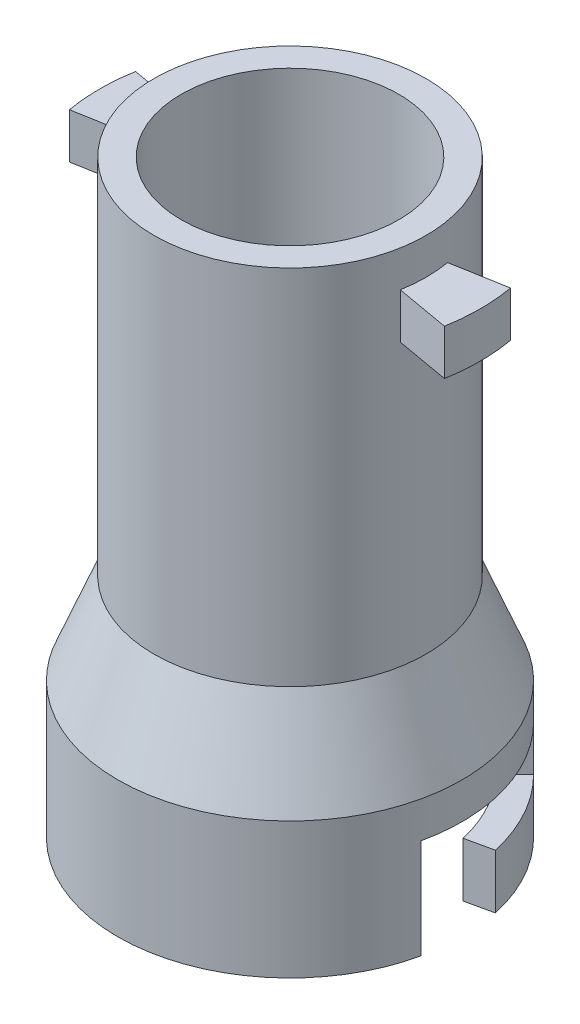
SolidWorks part; units mm, degrees
ref_plane "Front Plane" through (0, 0, 0) normal (0, 0, 1) x (1, 0, 0)
ref_plane "Top Plane" through (0, 0, 0) normal (0, 1, 0) x (1, 0, 0)
ref_plane "Right Plane" through (0, 0, 0) normal (1, 0, 0) x (0, 0, -1)
sketch "Sketch1" plane through (0, 0, 0) normal (0, 0, 1) x (1, 0, 0)
  line L0 (0, 40.4677) -> (0, -47.133) construction
  line L1 (12, 32) -> (12, -18)
  line L2 (16, -33) -> (19, -33)
  line L3 (19, -33) -> (19, -18)
  line L4 (19, -18) -> (15, -8)
  line L5 (15, -8) -> (15, 32)
  line L6 (15, 32) -> (12, 32)
  line L7 (12, -18) -> (16, -18)
  line L8 (16, -18) -> (16, -33)
  line L9 (-38.6492, 0) -> (68.272, 0) construction
  dimension "D1" = 3
  dimension "D2" = 16
  dimension "D3" = 15
  dimension "D4" = 3
  dimension "D5" = 15
  dimension "D6" = 10
  dimension "D7" = 50
  dimension "D8" = 32
revolve "Revolve1" add sketch "Sketch1" angle 360 about L0
ref_axis "Axis1" through (0, -42.0041, 0) along (0, 1, 0)
sketch "Sketch2" plane through (0, 0, 0) normal (0, 0, 1) x (1, 0, 0)
  line L0 (15, 28) -> (21, 28)
  line L1 (15, -8) -> (15, 32) construction
  line L2 (21, 28) -> (21, 23)
  line L3 (21, 23) -> (15, 23)
  line L4 (15, 23) -> (15, 28)
  line L5 (-15, 28) -> (-15, 23)
  line L6 (-15, 32) -> (-15, -8) construction
  line L7 (-15, 23) -> (-21, 23)
  line L8 (-21, 23) -> (-21, 28)
  line L9 (-21, 28) -> (-15, 28)
  line L10 (0, 45.3067) -> (0, -45.5409) construction
  line L11 (15, 32) -> (-15, 32) construction
  dimension "D1" = 6
  dimension "D2" = 6
  dimension "D3" = 5
  dimension "D4" = 4
revolve "Revolve2" add sketch "Sketch2" angle 20 mid plane about L10
sketch "Sketch3" plane through (0, 0, 0) normal (0, 0, 1) x (1, 0, 0)
  line L0 (-19, -18) -> (-19, -33) construction
  line L1 (-19, -23) -> (-16, -23)
  line L2 (-19, -23) -> (-19, -33)
  line L3 (-19, -33) -> (-16, -33)
  line L4 (-16, -23) -> (-16, -33)
  line L5 (-19, -33) -> (19, -33) construction
  line L7 (19, -33) -> (16, -33)
  line L8 (19, -33) -> (19, -22)
  line L9 (19, -22) -> (16, -22)
  line L10 (16, -33) -> (16, -22)
  line L14 (0, -11.0207) -> (0, -43.2503) construction
  line L15 (-16, -18) -> (16, -18) construction
  dimension "D1" = 10
  dimension "D2" = 4
revolve "Cut-Revolve1" cut sketch "Sketch3" angle 25 mid plane about L14
sketch "Sketch4" plane through (0, 0, 0) normal (0, 0, 1) x (1, 0, 0)
  line L0 (-19, -18) -> (-19, -23) construction
  line L1 (19, -22) -> (16, -22)
  line L2 (19, -22) -> (19, -27)
  line L3 (19, -27) -> (16, -27)
  line L4 (16, -22) -> (16, -27)
  line L5 (-16, -27) -> (-19, -27)
  line L6 (-16, -27) -> (-16, -23)
  line L7 (-16, -23) -> (-19, -23)
  line L8 (-19, -27) -> (-19, -23)
  dimension "D1" = 5
revolve "Cut-Revolve2" cut sketch "Sketch4" angle 45 about axis through (0, -42.0041, 0) along (0, 1, 0)
